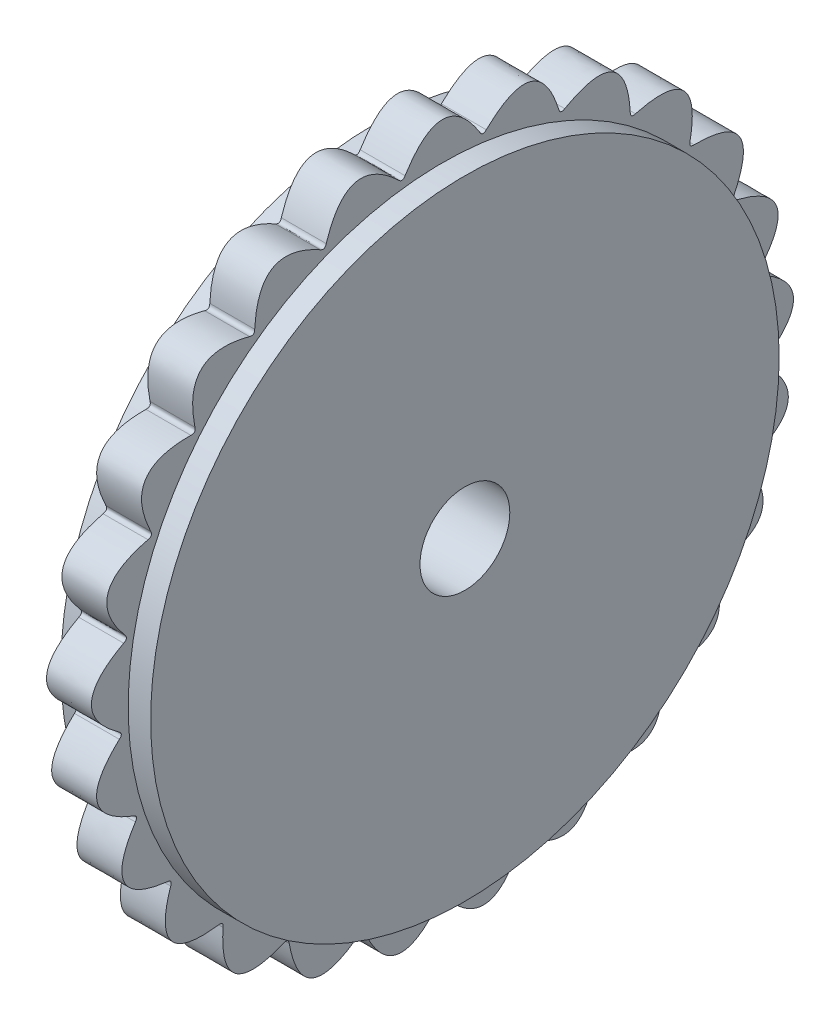
SolidWorks part; units mm, degrees
ref_plane "Front Plane" through (0, 0, 0) normal (0, 0, 1) x (1, 0, 0)
ref_plane "Top Plane" through (0, 0, 0) normal (0, 1, 0) x (1, 0, 0)
ref_plane "Right Plane" through (0, 0, 0) normal (1, 0, 0) x (0, 0, -1)
sketch "Sketch3" plane through (0, 0, 0) normal (1, 0, 0) x (0, 0, -1)
  line L0 (0, 21.5) -> (0, 23.5) construction
  line L1 (0, 21.5) -> (2.5, 21.5) construction
  line L2 (0, 21.5) -> (-2.5, 21.5) construction
  circle A0 centre (0, 0) radius 3
  spline S0 degree 2 poles (-2.5, 21.5) (0, 25.5) (2.5, 21.5) knots 0 0 0 1 1 1
  spline S1 degree 2 poles (2.9254, 21.4463) (6.3416, 24.6989) (7.7683, 20.2028) knots 0 0 0 1 1 1
  spline S2 degree 2 poles (8.1669, 20.045) (12.2847, 22.3458) (12.5485, 17.6362) knots 0 0 0 1 1 1
  spline S3 degree 2 poles (12.8953, 17.3842) (17.456, 18.5887) (16.5402, 13.9615) knots 0 0 0 1 1 1
  spline S4 degree 2 poles (16.8135, 13.6311) (21.5304, 13.6636) (19.4926, 9.4095) knots 0 0 0 1 1 1
  spline S5 degree 2 poles (19.6752, 9.0215) (24.2519, 7.8799) (21.2203, 4.2662) knots 0 0 0 1 1 1
  spline S6 degree 2 poles (21.3006, 3.8451) (25.4497, 1.6012) (21.6146, -1.1451) knots 0 0 0 1 1 1
  spline S7 degree 2 poles (21.5876, -1.573) (25.0483, -4.7782) (20.6507, -6.4844) knots 0 0 0 1 1 1
  spline S8 degree 2 poles (20.5182, -6.8922) (23.0731, -10.8574) (18.3893, -11.4163) knots 0 0 0 1 1 1
  spline S9 degree 2 poles (18.1596, -11.7783) (19.6481, -16.2543) (14.9725, -15.6309) knots 0 0 0 1 1 1
  spline S10 degree 2 poles (14.6599, -15.9244) (14.9885, -20.6299) (10.6148, -18.8633) knots 0 0 0 1 1 1
  spline S11 degree 2 poles (10.2391, -19.0699) (9.3872, -23.7093) (5.5902, -20.9105) knots 0 0 0 1 1 1
  spline S12 degree 2 poles (5.175, -21.0171) (3.196, -25.2989) (0.2144, -21.6438) knots 0 0 0 1 1 1
  spline S13 degree 2 poles (-0.2144, -21.6438) (-3.196, -25.2989) (-5.175, -21.0171) knots 0 0 0 1 1 1
  spline S14 degree 2 poles (-5.5902, -20.9105) (-9.3872, -23.7093) (-10.2391, -19.0699) knots 0 0 0 1 1 1
  spline S15 degree 2 poles (-10.6148, -18.8633) (-14.9885, -20.6299) (-14.6599, -15.9244) knots 0 0 0 1 1 1
  spline S16 degree 2 poles (-14.9725, -15.6309) (-19.6481, -16.2543) (-18.1596, -11.7783) knots 0 0 0 1 1 1
  spline S17 degree 2 poles (-18.3893, -11.4163) (-23.0731, -10.8574) (-20.5182, -6.8922) knots 0 0 0 1 1 1
  spline S18 degree 2 poles (-20.6507, -6.4844) (-25.0483, -4.7782) (-21.5876, -1.573) knots 0 0 0 1 1 1
  spline S19 degree 2 poles (-21.6146, -1.1451) (-25.4497, 1.6012) (-21.3006, 3.8451) knots 0 0 0 1 1 1
  spline S20 degree 2 poles (-21.2203, 4.2662) (-24.2519, 7.8799) (-19.6752, 9.0215) knots 0 0 0 1 1 1
  spline S21 degree 2 poles (-19.4926, 9.4095) (-21.5304, 13.6636) (-16.8135, 13.6311) knots 0 0 0 1 1 1
  spline S22 degree 2 poles (-16.5402, 13.9615) (-17.456, 18.5887) (-12.8953, 17.3842) knots 0 0 0 1 1 1
  spline S23 degree 2 poles (-12.5485, 17.6362) (-12.2847, 22.3458) (-8.1669, 20.045) knots 0 0 0 1 1 1
  spline S24 degree 2 poles (-7.7683, 20.2028) (-6.3416, 24.6989) (-2.9254, 21.4463) knots 0 0 0 1 1 1
  spline S25 degree 2 poles (-2.9254, 21.4463) (-2.6709, 21.1883) (-2.5, 21.5) knots 0 0 0 1 1 1
  spline S26 degree 2 poles (2.5, 21.5) (2.6823, 21.1868) (2.9254, 21.4463) knots 0 0 0 1 1 1
  spline S27 degree 2 poles (7.7683, 20.2028) (7.867, 19.8541) (8.1669, 20.045) knots 0 0 0 1 1 1
  spline S28 degree 2 poles (12.5485, 17.6362) (12.5574, 17.2739) (12.8953, 17.3842) knots 0 0 0 1 1 1
  spline S29 degree 2 poles (16.5402, 13.9615) (16.4587, 13.6084) (16.8135, 13.6311) knots 0 0 0 1 1 1
  spline S30 degree 2 poles (19.4926, 9.4095) (19.3259, 9.0877) (19.6752, 9.0215) knots 0 0 0 1 1 1
  spline S31 degree 2 poles (21.2203, 4.2662) (20.9787, 3.9961) (21.3006, 3.8451) knots 0 0 0 1 1 1
  spline S32 degree 2 poles (21.6146, -1.1451) (21.3134, -1.3467) (21.5876, -1.573) knots 0 0 0 1 1 1
  spline S33 degree 2 poles (20.6507, -6.4844) (20.3089, -6.6048) (20.5182, -6.8922) knots 0 0 0 1 1 1
  spline S34 degree 2 poles (18.3893, -11.4163) (18.0283, -11.4479) (18.1596, -11.7783) knots 0 0 0 1 1 1
  spline S35 degree 2 poles (14.9725, -15.6309) (14.615, -15.5717) (14.6599, -15.9244) knots 0 0 0 1 1 1
  spline S36 degree 2 poles (10.6148, -18.8633) (10.2833, -18.7171) (10.2391, -19.0699) knots 0 0 0 1 1 1
  spline S37 degree 2 poles (5.5902, -20.9105) (5.3054, -20.6864) (5.175, -21.0171) knots 0 0 0 1 1 1
  spline S38 degree 2 poles (0.2144, -21.6438) (-0.0057, -21.3559) (-0.2144, -21.6438) knots 0 0 0 1 1 1
  spline S39 degree 2 poles (-5.175, -21.0171) (-5.3166, -20.6836) (-5.5902, -20.9105) knots 0 0 0 1 1 1
  spline S40 degree 2 poles (-10.2391, -19.0699) (-10.2933, -18.7116) (-10.6148, -18.8633) knots 0 0 0 1 1 1
  spline S41 degree 2 poles (-14.6599, -15.9244) (-14.6233, -15.5639) (-14.9725, -15.6309) knots 0 0 0 1 1 1
  spline S42 degree 2 poles (-18.1596, -11.7783) (-18.0345, -11.4382) (-18.3893, -11.4163) knots 0 0 0 1 1 1
  spline S43 degree 2 poles (-20.5182, -6.8922) (-20.3125, -6.5939) (-20.6507, -6.4844) knots 0 0 0 1 1 1
  spline S44 degree 2 poles (-21.5876, -1.573) (-21.3142, -1.3352) (-21.6146, -1.1451) knots 0 0 0 1 1 1
  spline S45 degree 2 poles (-21.3006, 3.8451) (-20.9766, 4.0073) (-21.2203, 4.2662) knots 0 0 0 1 1 1
  spline S46 degree 2 poles (-19.6752, 9.0215) (-19.321, 9.0981) (-19.4926, 9.4095) knots 0 0 0 1 1 1
  spline S47 degree 2 poles (-16.8135, 13.6311) (-16.4514, 13.6172) (-16.5402, 13.9615) knots 0 0 0 1 1 1
  spline S48 degree 2 poles (-12.8953, 17.3842) (-12.5481, 17.2807) (-12.5485, 17.6362) knots 0 0 0 1 1 1
  spline S49 degree 2 poles (-8.1669, 20.045) (-7.8563, 19.8584) (-7.7683, 20.2028) knots 0 0 0 1 1 1
  point P84 (0, 0)
  point P158 (0, 0)
  dimension "D1" = 6
  dimension "D4" = 2.5
  dimension "D5" = 2.5
extrude "Boss-Extrude1" add sketch "Sketch3" along normal blind 3 contours S49 S23 S48 S22 S47 S21 S46 S20 S45 S19 S44 S18 S43 S17 S42 S16 S41 S15 S40 S14 S39 S13 S38 S12 S37 S11 S36 S10 S35 S9 S34 S8 S33 S7 S32 S6 S31 S5 S30 S4 S29 S3 S28 S2 S27 S1 S26 S0 S25 S24
sketch "Sketch5" plane through (3, 0, 0) normal (1, 0, 0) x (0, 0, -1)
  circle A0 centre (0, 0) radius 21
  circle A1 centre (0, 0) radius 3
extrude "Boss-Extrude2" add sketch "Sketch5" along normal blind 1.5
sketch "Sketch6" plane through (0, 0, 0) normal (-1, 0, 0) x (0, 0, 1)
  circle A0 centre (0, 0) radius 21
  circle A1 centre (0, 0) radius 3
extrude "Boss-Extrude3" add sketch "Sketch6" along normal blind 1.5
